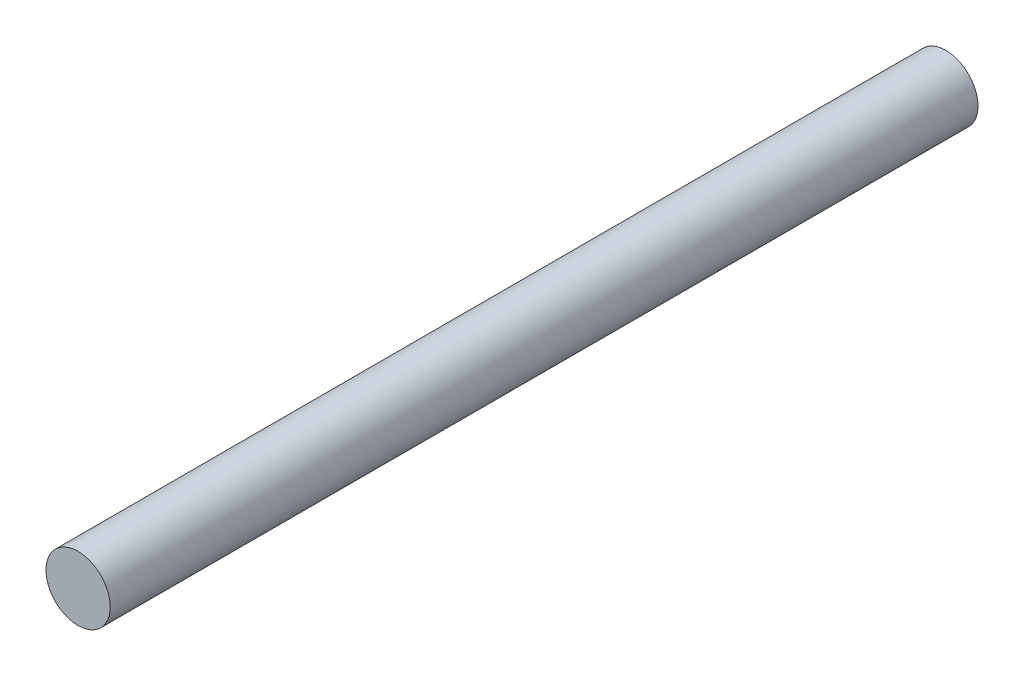
SolidWorks part; units mm, degrees
ref_plane "Front Plane" through (0, 0, 0) normal (0, 0, 1) x (1, 0, 0)
ref_plane "Top Plane" through (0, 0, 0) normal (0, 1, 0) x (1, 0, 0)
ref_plane "Right Plane" through (0, 0, 0) normal (1, 0, 0) x (0, 0, -1)
sketch "Sketch1" plane through (0, 0, 0) normal (0, 0, 1) x (1, 0, 0)
  circle A0 centre (0, 0) radius 25.4
  dimension "D1" = 50.8
extrude "Boss-Extrude1" add sketch "Sketch1" along normal blind 685.8
